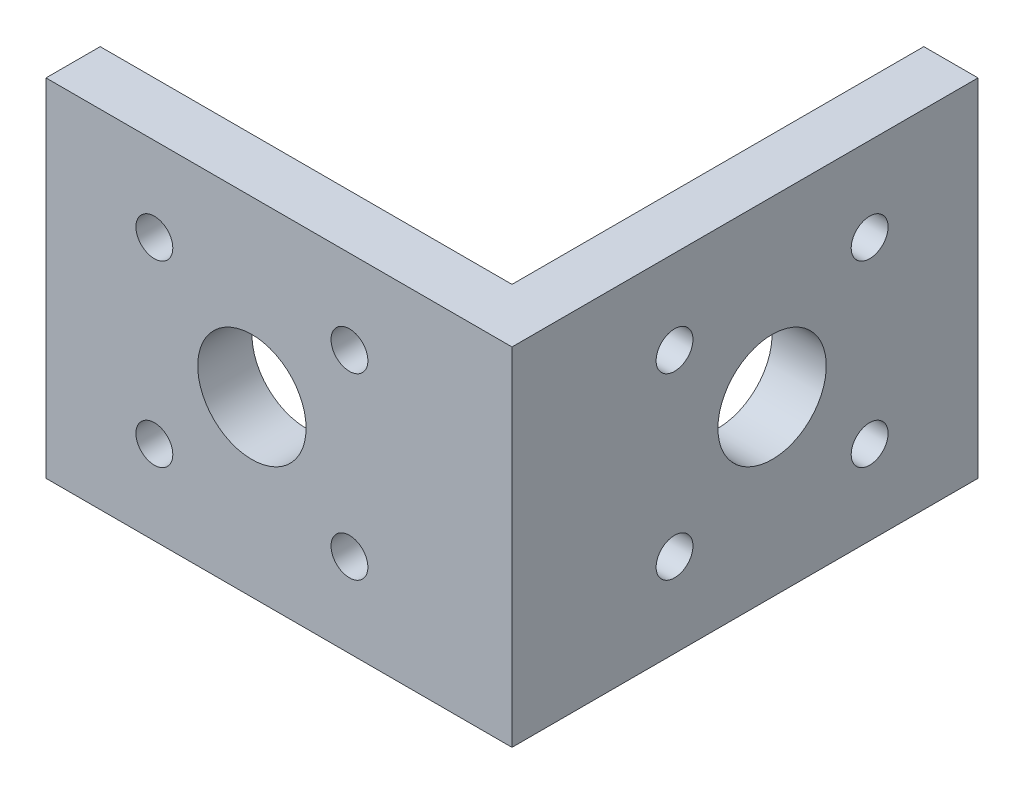
SolidWorks part; units mm, degrees
ref_plane "Front Plane" through (0, 0, 0) normal (0, 0, 1) x (1, 0, 0)
ref_plane "Top Plane" through (0, 0, 0) normal (0, 1, 0) x (1, 0, 0)
ref_plane "Right Plane" through (0, 0, 0) normal (1, 0, 0) x (0, 0, -1)
sketch "Sketch1" plane through (0, 0, 0) normal (0, 0, 1) x (1, 0, 0)
  line L1 (-19, 16) -> (19, 16)
  line L2 (-19, 16) -> (-19, -16)
  line L3 (-19, -16) -> (19, -16)
  line L4 (19, 16) -> (19, -16)
  circle A0 centre (0, 0) radius 5
  circle A1 centre (-9, 8.25) radius 1.7
  circle A2 centre (9, 8.25) radius 1.7
  circle A3 centre (9, -8.25) radius 1.7
  circle A4 centre (-9, -8.25) radius 1.7
  point P0 (0, 0)
  dimension "D3" = 16
  dimension "D4" = 19
  dimension "D5" = 9
  dimension "D6" = 8.25
  dimension "D1" = 32
  dimension "D2" = 38
  dimension "D7" = 2
  dimension "D8" = 2
extrude "Boss-Extrude1" add sketch "Sketch1" along normal blind 5
sketch "Sketch2" plane through (0, 0, 0) normal (0, 0, 1) x (1, 0, 0)
  line L2 (19, 16) -> (24, 16)
  line L3 (19, 16) -> (19, -16)
  line L4 (19, -16) -> (24, -16)
  line L5 (24, 16) -> (24, -16)
  dimension "D1" = 5
  dimension "D2" = 32
ref_plane "Plane2" through (19, 0, 0) normal (1, 0, 0) x (0, 0, -1)
ref_plane "Plane3" through (9.5, 0, -9.5) normal (0.7071, 0, -0.7071) x (-0.7071, 0, -0.7071)
extrude "Boss-Extrude4" add sketch "Sketch2" along normal blind 5
mirror "Mirror3" about plane through (9.5, 0, -9.5) normal (0.7071, 0, -0.7071) of "Boss-Extrude1"
